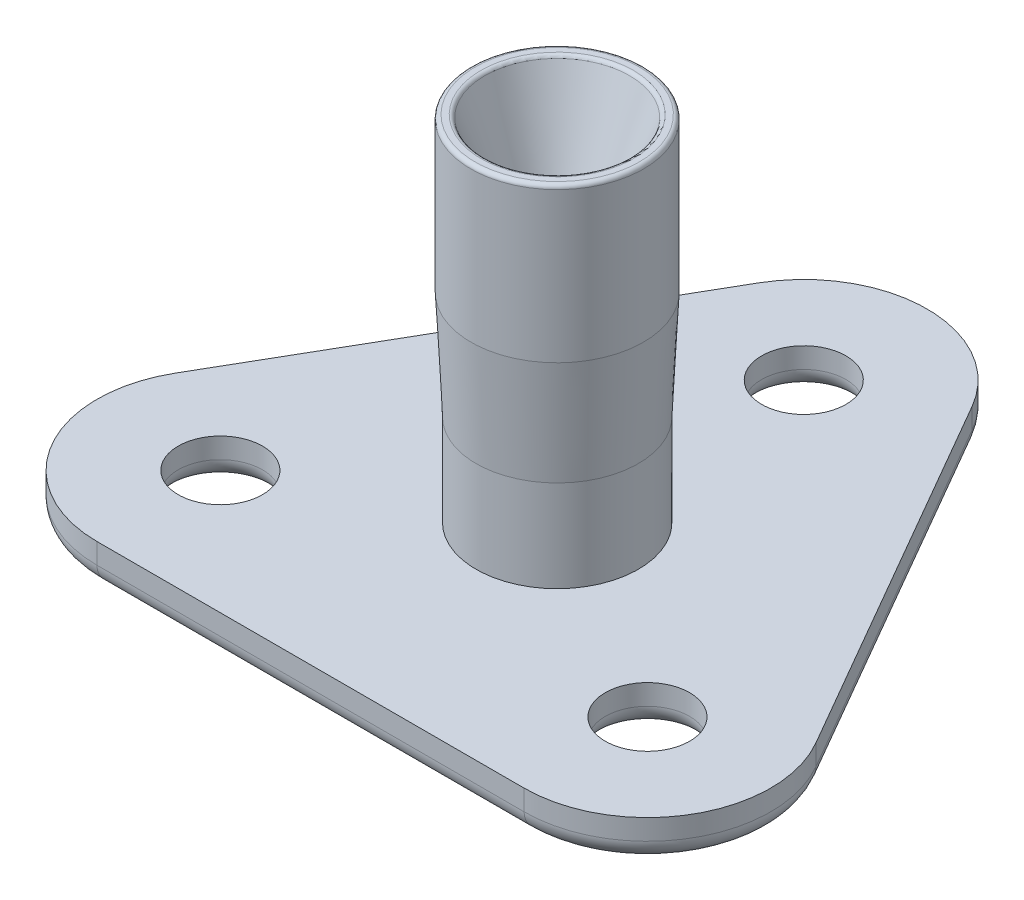
SolidWorks part; units mm, degrees
ref_plane "Front Plane" through (0, 0, 0) normal (0, 0, 1) x (1, 0, 0)
ref_plane "Top Plane" through (0, 0, 0) normal (0, 1, 0) x (1, 0, 0)
ref_plane "Right Plane" through (0, 0, 0) normal (1, 0, 0) x (0, 0, -1)
sketch "Sketch1" plane through (0, 0, 0) normal (0, 0, 1) x (1, 0, 0)
  line L0 (0, 0) -> (0, 25)
  line L2 (-4.2, 19.1942) -> (-4.2, 11.6977)
  line L3 (-4.2, 11.6977) -> (-3.95, 6.4551)
  line L4 (-3.95, 6.4551) -> (-3.95, 2)
  line L5 (-3.95, 2) -> (-8, 2)
  line L6 (-8, 2) -> (-8, 0)
  line L7 (-8, 0) -> (-2.8073, 0)
  line L8 (-2.8073, 0) -> (-1.05, 2)
  line L9 (-1.05, 2) -> (-1.05, 12.2419)
  line L10 (-1.05, 12.2419) -> (-3.5765, 19.1942)
  line L11 (-3.5765, 19.1942) -> (-4.2, 19.1942)
  point P4 (-4.7041, 7.8528)
  point P11 (-1.05, 15.8953)
  point P15 (-3.6419, 23.0273)
  point P16 (0, 0)
  point P17 (0, 0)
  point P18 (0, 0)
  point P19 (0, 0)
  point P20 (-4.2, 11.6977)
  point P21 (-3.95, 6.4551)
  dimension "D1" = 25
  dimension "D2" = 2
  dimension "D3" = 1.05
  dimension "D4" = 8
  dimension "D5" = 3.95
  dimension "D6" = 4.2
revolve "Revolve1" add sketch "Sketch1" angle 360 about L0
sketch "Sketch2" plane through (0, 0, 0) normal (0, 1, 0) x (1, 0, 0)
  line L0 (-10.3923, -12) -> (10.3923, -12)
  line L1 (-15.5885, -3) -> (-5.1962, 15)
  line L2 (15.5885, -3) -> (5.1962, 15)
  circle A0 centre (0, 12) radius 2.05
  circle A1 centre (0, 12) radius 6
  circle A2 centre (10.3923, -6) radius 6
  circle A3 centre (10.3923, -6) radius 2.05
  circle A4 centre (-10.3923, -6) radius 6
  circle A5 centre (-10.3923, -6) radius 2.05
  circle A6 centre (0, 0) radius 3
  point P12 (0, 0)
  dimension "D1" = 4.1
  dimension "D3" = 12
  dimension "D5" = 6
  dimension "D2" = 12
  dimension "D4" = 3
extrude "Boss-Extrude1" add sketch "Sketch2" along normal up to surface (2 mm away) contours A4 L0 A2 L2 A1 L1 | A2 A3 | A4 A5 | A1 A0
fillet "Fillet3" radius 0.2 2 edges at (0, 19.1942, -3.5765) (0, 19.1942, -4.2)
fillet "Fillet4" radius 1 10 edges at (-15.5885, 0, 9) (0, 0, 12) (15.5885, 0, 9) (10.3923, 0, -6) (0, 0, -18) (-10.3923, 0, -6) (0, 0, -9.95) (10.3923, 0, 8.05) (-10.3923, 0, 8.05) (0, 0, -2.8073)
